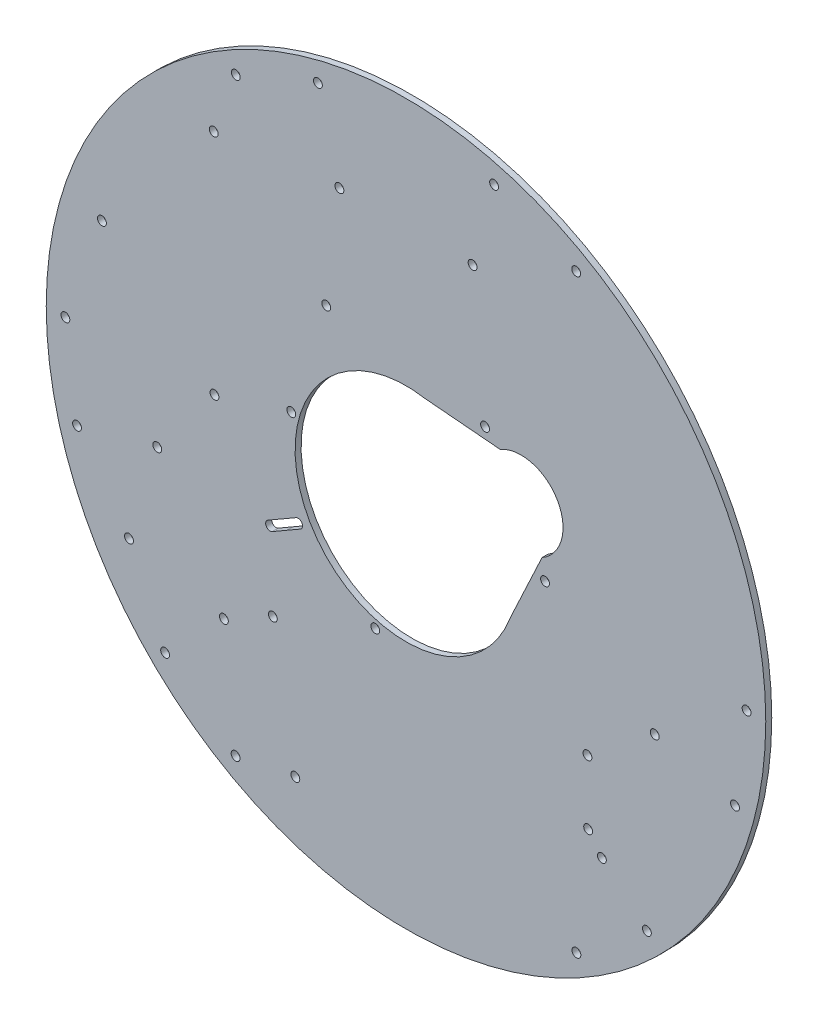
SolidWorks part; units mm, degrees
ref_plane "Front Plane" through (0, 0, 0) normal (0, 0, 1) x (1, 0, 0)
ref_plane "Top Plane" through (0, 0, 0) normal (0, 1, 0) x (1, 0, 0)
ref_plane "Right Plane" through (0, 0, 0) normal (1, 0, 0) x (0, 0, -1)
sketch "Sketch1" plane through (0, 0, 0) normal (0, 0, 1) x (1, 0, 0)
  line L0 (-29.696, 44.1657) -> (8.6839, 66.3243)
  line L1 (8.6839, 66.3243) -> (14.5487, 56.1662)
  line L2 (8.6839, 66.3243) -> (2.8191, 76.4825)
  line L3 (14.5487, 56.1662) -> (15.6839, 54.2)
  line L4 (-29.696, 44.1657) -> (-18.4089, -19.8468)
  line L5 (2.8191, 76.4825) -> (1.6839, 78.4487)
  line L6 (-108.5986, 110.3728) -> (-87.1493, 92.3748)
  line L7 (-87.1493, 92.3748) -> (-29.696, 44.1657)
  line L8 (-122.0909, -9.1786) -> (-70.1294, 20.8214)
  line L9 (15.6839, 54.2) -> (2.3469, 25.6657)
  line L10 (-18.4089, -19.8468) -> (38.2176, -9.862)
  line L11 (1.6839, 78.4487) -> (-29.696, 81.1657)
  line L12 (-29.696, 81.1657) -> (2.3469, 25.6657)
  line L15 (38.2176, -9.862) -> (33.8164, 15.0985)
  line L19 (-70.1294, 20.8214) -> (-29.696, 44.1657)
  line L20 (-108.5986, 110.3728) -> (-81.4117, 142.7728)
  line L21 (-81.4117, 142.7728) -> (-38.5132, 106.7767)
  line L22 (-93.1502, 41.6629) -> (-136.0487, 77.6591)
  line L23 (-136.0487, 77.6591) -> (-108.5986, 110.3728)
  line L24 (-136.0487, 77.6591) -> (-133.7989, 80.3402)
  line L25 (-133.7989, 80.3402) -> (-131.1178, 78.0905)
  line L26 (-93.1502, 41.6629) -> (-90.9004, 44.3441)
  line L27 (-90.9004, 44.3441) -> (-38.5132, 106.7767)
  line L28 (-90.9004, 44.3441) -> (-93.5816, 46.5939)
  line L29 (-131.1178, 78.0905) -> (-93.8361, 122.521)
  line L30 (-93.8361, 122.521) -> (-56.2999, 91.0244)
  line L31 (-93.5816, 46.5939) -> (-56.2999, 91.0244)
  line L33 (-70.1294, 20.8214) -> (-69.3919, 19.5441)
  line L34 (-65.672, 23.3949) -> (-66.4095, 24.6723)
  line L35 (-75.0279, 17.9933) -> (-74.2904, 16.7159)
  line L36 (-74.2904, 16.7159) -> (-69.3919, 19.5441)
  line L37 (-69.3919, 19.5441) -> (-64.9345, 22.1176)
  line L38 (-66.4095, 24.6723) -> (-70.8669, 22.0988)
  line L39 (-75.0279, 17.9933) -> (-75.7654, 19.2707)
  line L40 (-75.7654, 19.2707) -> (-70.8669, 22.0988)
  line L43 (33.8164, 15.0985) -> (29.1385, 14.2737)
  line L44 (29.1385, 14.2737) -> (30.8316, 4.6718)
  line L45 (-18.4089, -19.8468) -> (-75.0353, -29.8316)
  line L46 (-75.0353, -29.8316) -> (-79.4365, -4.871)
  line L47 (-79.4365, -4.871) -> (-74.7587, -4.0462)
  line L48 (-75.0353, -29.8316) -> (-70.6341, -54.7921)
  line L49 (-70.6341, -54.7921) -> (-65.9562, -53.9673)
  line L50 (-65.9562, -53.9673) -> (-66.6074, -50.2743)
  line L51 (38.2176, -9.862) -> (42.6188, -34.8226)
  line L52 (42.6188, -34.8226) -> (37.941, -35.6474)
  line L53 (37.941, -35.6474) -> (35.6401, -22.5987)
  line L54 (-74.7587, -4.0462) -> (-74.1075, -7.7392)
  circle A0 centre (-29.696, 44.1657) radius 120.0027
  circle A1 centre (-59.0776, 153.9087) radius 1.475
  circle A2 centre (-86.4628, 142.5747) radius 1.475
  circle A3 centre (-0.3144, 153.9087) radius 1.475
  circle A4 centre (27.0708, 142.5747) radius 1.475
  circle A5 centre (-7.4824, 127.1357) radius 1.475
  circle A6 centre (-51.9096, 127.1357) radius 1.475
  circle A7 centre (-143.3041, 44.1227) radius 1.475
  circle A8 centre (-139.427, 14.7394) radius 1.475
  circle A9 centre (-110.0454, -36.151) radius 1.475
  circle A10 centre (-86.5373, -54.2003) radius 1.475
  circle A11 centre (-112.6569, 21.9182) radius 1.475
  circle A12 centre (-90.4433, -16.5569) radius 1.475
  circle A13 centre (83.9121, 44.1227) radius 1.475
  circle A14 centre (80.035, 14.7394) radius 1.475
  circle A15 centre (50.6534, -36.151) radius 1.475
  circle A16 centre (27.1453, -54.2003) radius 1.475
  circle A17 centre (53.2649, 21.9182) radius 1.475
  circle A18 centre (31.0513, -16.5569) radius 1.475
  circle A19 centre (-3.3229, 82.4862) radius 1.475
  circle A20 centre (16.6771, 47.8452) radius 1.475
  circle A21 centre (-67.9447, 54.4144) radius 1.475
  circle A22 centre (-39.9447, 5.917) radius 1.475
  circle A23 centre (-29.696, 44.1657) radius 37
  circle A24 centre (8.6839, 66.3243) radius 11.7296
  circle A25 centre (-131.1178, 78.0905) radius 1.475
  circle A26 centre (-93.5816, 46.5939) radius 1.475
  circle A27 centre (-93.8361, 122.521) radius 1.475
  circle A28 centre (-56.2999, 91.0244) radius 1.475
  circle A33 centre (-122.0909, -9.1786) radius 1.475
  circle A34 centre (-70.1294, 20.8214) radius 1.475
  circle A35 centre (-65.672, 23.3949) radius 1.475
  circle A36 centre (-75.0279, 17.9933) radius 1.475
  circle A46 centre (35.6401, -22.5987) radius 1.475
  circle A47 centre (30.8316, 4.6718) radius 1.475
  circle A48 centre (-66.6074, -50.2743) radius 1.475
  circle A49 centre (-74.1075, -7.7392) radius 1.475
  circle A50 centre (8.6839, 66.3243) radius 14
  point P57 (0, 0)
  point P64 (0, 0)
  point P67 (0, 0)
  point P78 (-87.1493, 92.3748)
extrude "Boss-Extrude1" add sketch "Sketch1" along normal blind 2
